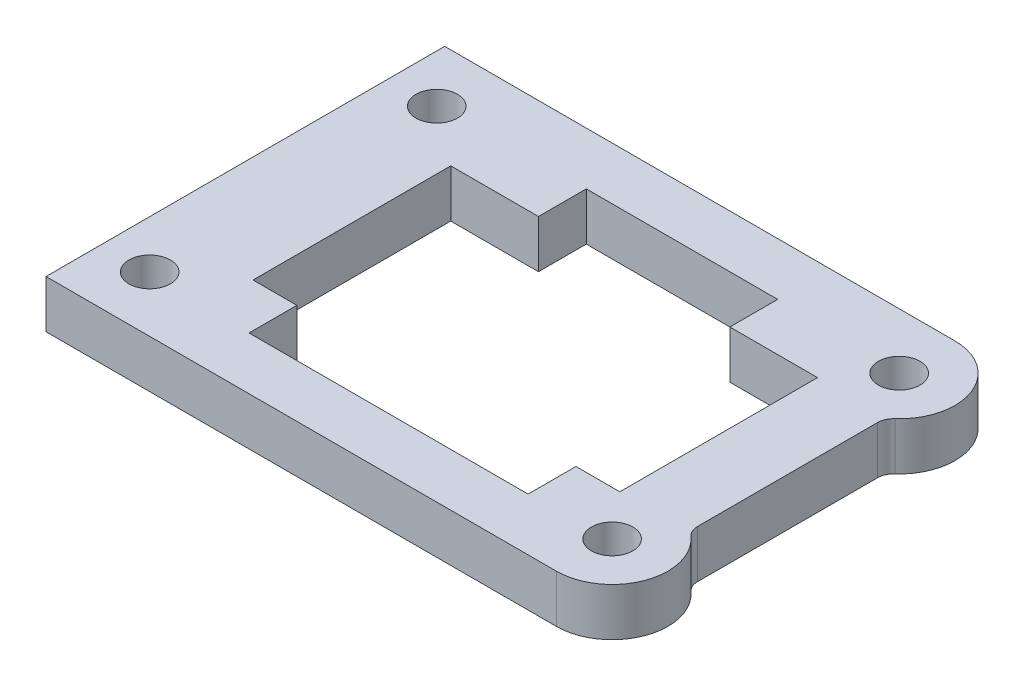
SolidWorks part; units mm, degrees
material "Acrílico (médio-alto impacto)"
ref_plane "Plano frontal" through (0, 0, 0) normal (0, 0, 1) x (1, 0, 0)
ref_plane "Plano superior" through (0, 0, 0) normal (0, 1, 0) x (1, 0, 0)
ref_plane "Plano direito" through (0, 0, 0) normal (1, 0, 0) x (0, 0, -1)
sketch "Perfil Principal" plane through (0, 0, 0) normal (0, 1, 0) x (1, 0, 0)
  line L1 (-17.5, -12.5) -> (17.5, -12.5)
  line L2 (-17.5, -12.5) -> (-17.5, 12.5)
  line L3 (-17.5, 12.5) -> (17.5, 12.5)
  line L4 (17.5, -12.5) -> (17.5, 12.5)
  line L5 (0, 12.5) -> (0, -12.5) construction
  line L6 (-17.5, 0) -> (17.5, 0) construction
  point P0 (0, 0)
  dimension "D1" = 35
  dimension "D2" = 25
sketch "Posições Furos" plane through (0, 0, 0) normal (0, 1, 0) x (1, 0, 0)
  line L0 (-17.5, 0) -> (17.5, 0) construction
  line L1 (-14.5, 9) -> (14.5, 9) construction
  line L2 (-14.5, 9) -> (-14.5, -9) construction
  line L3 (-14.5, -9) -> (14.5, -9) construction
  line L5 (0, -9) -> (0, 9) construction
  line L6 (-14.5, 0) -> (14.5, 0) construction
  line L11 (14.5, 9) -> (14.5, -9) construction
  line L14 (-17.5, -12.5) -> (-17.5, 12.5) construction
  point P0 (0, 0)
  dimension "D1" = 29
  dimension "D2" = 18
  dimension "D4" = 3
sketch "Base Perfil" plane through (0, 0, 0) normal (0, 1, 0) x (1, 0, 0)
  line L0 (-17.5, 12.5) -> (17.5, 12.5) construction
  line L1 (-17.5, 12.5) -> (14.5, 12.5)
  line L2 (-17.5, -12.5) -> (17.5, -12.5) construction
  line L3 (-17.5, -12.5) -> (14.5, -12.5)
  line L4 (16.5, 5.6459) -> (16.5, -5.6459)
  line L6 (17.5, -12.5) -> (17.5, 12.5) construction
  line L7 (-17.5, 12.5) -> (-17.5, -12.5) construction
  line L8 (-17.5, 12.5) -> (-17.5, -12.5)
  arc A0 (14.5, 12.5) -> (16.8333, 6.3913) centre (14.5, 9) cw
  arc A1 (16.8333, 6.3913) -> (16.5, 5.6459) centre (17.5, 5.6459) ccw
  arc A2 (16.5, -5.6459) -> (16.8333, -6.3913) centre (17.5, -5.6459) ccw
  arc A3 (16.8333, -6.3913) -> (14.5, -12.5) centre (14.5, -9) cw
  dimension "D1" = 1
  dimension "D2" = 1
extrude "Ressalto-extrusão1" add sketch "Base Perfil" along normal blind 3 contours L4 A2 A3 L3 L8 L1 A0 A1
sketch "Perfil Corte" plane through (-89.3092, 3, 15.8051) normal (0, 1, 0) x (1, 0, 0)
  line L0 (89.9892, 5.8051) -> (89.9892, 25.8051) construction
  line L1 (78.4892, 9.6051) -> (101.4892, 9.6051)
  line L2 (78.4892, 9.6051) -> (78.4892, 22.0051)
  line L3 (78.4892, 22.0051) -> (101.4892, 22.0051)
  line L4 (101.4892, 9.6051) -> (101.4892, 22.0051)
  line L5 (89.9892, 22.0051) -> (89.9892, 9.6051) construction
  line L6 (78.4892, 15.8051) -> (101.4892, 15.8051) construction
  line L7 (101.4892, 15.8051) -> (105.8092, 15.8051) construction
  line L8 (105.8092, 10.1592) -> (105.8092, 21.451) construction
  line L9 (103.8092, 28.3051) -> (71.8092, 28.3051) construction
  point P0 (89.9892, 15.8051)
  point P7 (89.9892, 15.8051)
  dimension "D1" = 23
  dimension "entre furos" = 20
  dimension "D2" = 12.4
  dimension "Afastamento Lateral" = 15.82
  dimension "Posicionamento Altura" = 12.5
extrude "Corte Principal" cut sketch "Perfil Corte" against normal through all
sketch "Esboço7" plane through (-37.6306, 3, 29.5975) normal (0, 1, 0) x (1, 0, 0)
  line L0 (38.3106, 19.5975) -> (38.3106, 39.5975) construction
  line L1 (32.3106, 38.7975) -> (44.3106, 38.7975)
  line L2 (32.3106, 38.7975) -> (32.3106, 35.7975)
  line L3 (32.3106, 35.7975) -> (44.3106, 35.7975)
  line L4 (44.3106, 38.7975) -> (44.3106, 35.7975)
  line L5 (38.3106, 35.7975) -> (38.3106, 38.7975) construction
  line L6 (32.3106, 37.2975) -> (44.3106, 37.2975) construction
  line L7 (26.8106, 35.7975) -> (49.8106, 35.7975) construction
  line L8 (26.8106, 23.3975) -> (26.8106, 35.7975) construction
  line L9 (26.8106, 23.3975) -> (49.8106, 23.3975) construction
  line L10 (29.5606, 20.3975) -> (47.0606, 20.3975)
  line L11 (29.5606, 20.3975) -> (29.5606, 23.3975)
  line L12 (29.5606, 23.3975) -> (47.0606, 23.3975)
  line L13 (47.0606, 20.3975) -> (47.0606, 23.3975)
  line L14 (38.3106, 23.3975) -> (38.3106, 20.3975) construction
  line L15 (29.5606, 21.8975) -> (47.0606, 21.8975) construction
  point P0 (38.3106, 37.2975)
  point P10 (38.3106, 21.8975)
  dimension "D1" = 3
  dimension "D2" = 5.5
  dimension "D3" = 17.5
  dimension "D4" = 12
extrude "Corte-extrusão3" cut sketch "Esboço7" against normal through all
other "Furos Motor<1>"
hole_wizard "Furo de diâmetro Ø2.6 (2.6)1" positions "Esboço10" profile "Esboço11" hole size "Ø2.6" standard "ISO" end condition through all
sketch "Esboço10" plane through (0, 3, 0) normal (0, 1, 0) x (1, 0, 0)
  point P0 (-14.5, 9)
  point P3 (-14.5, -9)
  point P6 (14.5, 9)
  point P9 (14.5, -9)
sketch "Esboço11" plane through (-14.5, 3, -9) normal (1, 0, 0) x (0, 0, 1)
  line L0 (0, 0) -> (0, 3)
  line L1 (0, 3) -> (1.3, 3)
  line L2 (1.3, 3) -> (1.3, 0)
  line L5 (1.3, 0) -> (0, 0)
  line L11 (0, -6.35) -> (0, 107.95) construction
  dimension "Thru Hole Dia." = 2.6
  dimension "Thru Hole Depth" = 3
